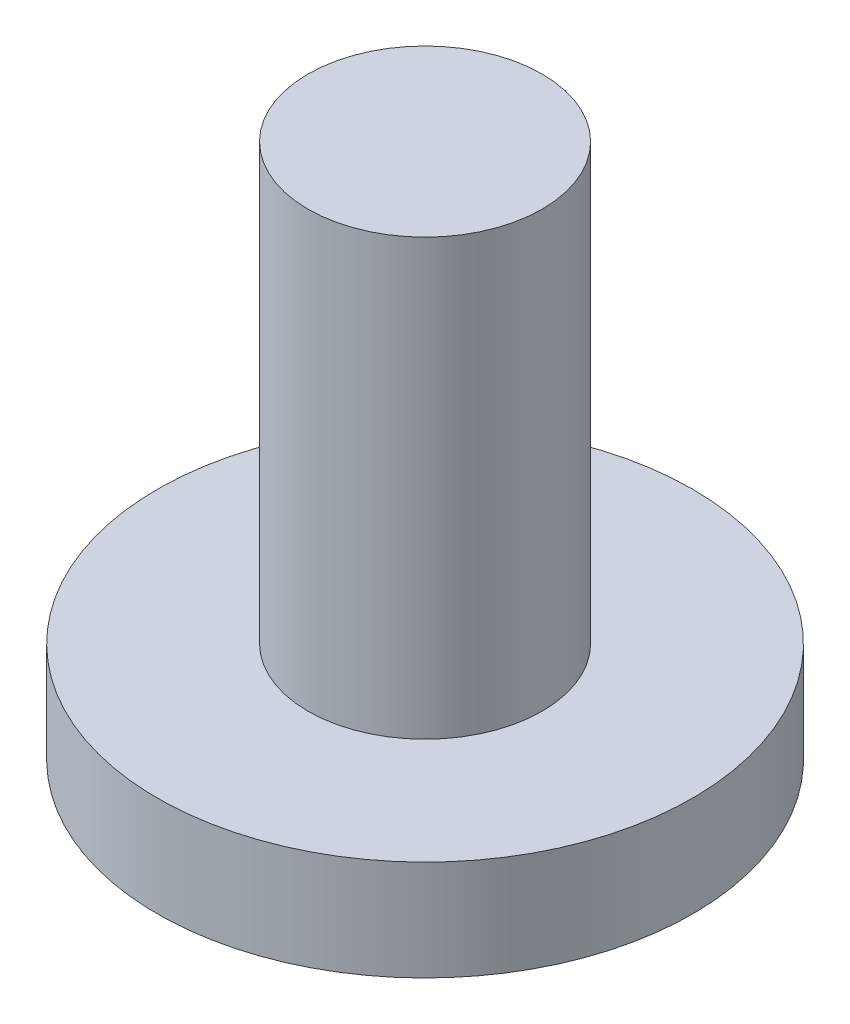
SolidWorks part; units mm, degrees
ref_plane "Front Plane" through (0, 0, 0) normal (0, 0, 1) x (1, 0, 0)
ref_plane "Top Plane" through (0, 0, 0) normal (0, 1, 0) x (1, 0, 0)
ref_plane "Right Plane" through (0, 0, 0) normal (1, 0, 0) x (0, 0, -1)
sketch "Sketch1" plane through (0, 0, 0) normal (0, 1, 0) x (1, 0, 0)
  circle A0 centre (0, 0) radius 1.75
extrude "Boss-Extrude1" add sketch "Sketch1" along normal blind 8
sketch "Sketch2" plane through (0, 0, 0) normal (0, -1, 0) x (1, 0, 0)
  circle A0 centre (0, 0) radius 4
extrude "Boss-Extrude2" add sketch "Sketch2" against normal blind 1.5
